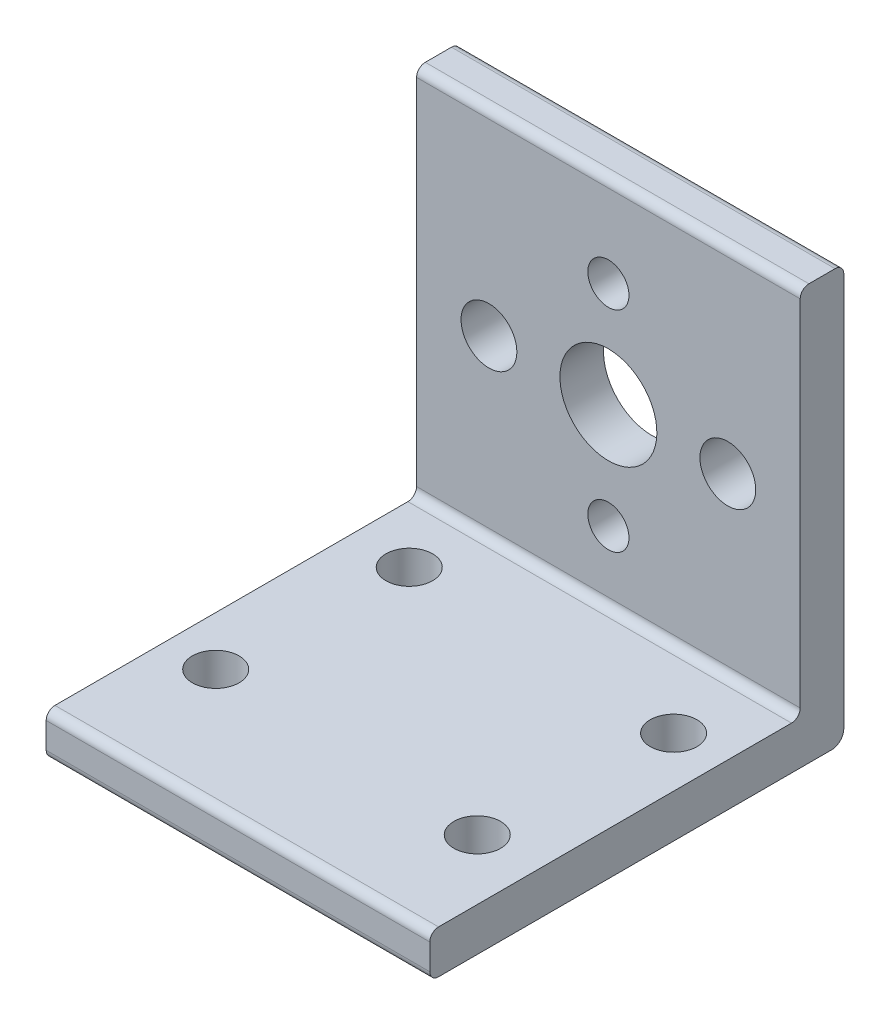
SolidWorks part; units mm, degrees
material "6061-T6 (SS)"
ref_plane "Front Plane" through (0, 0, 0) normal (0, 0, 1) x (1, 0, 0)
ref_plane "Top Plane" through (0, 0, 0) normal (0, 1, 0) x (1, 0, 0)
ref_plane "Right Plane" through (0, 0, 0) normal (1, 0, 0) x (0, 0, -1)
sketch "Sketch1" plane through (0, 0, 0) normal (1, 0, 0) x (0, 0, -1)
  line L0 (0, 0) -> (0, -30.226)
  line L1 (0, -30.226) -> (-30.1498, -30.226)
  line L2 (-30.1498, -30.226) -> (-30.1498, -27.0764)
  line L3 (-30.1498, -27.0764) -> (-3.175, -27.0764)
  line L4 (-3.175, -27.0764) -> (-3.175, 0)
  line L5 (-3.175, 0) -> (0, 0)
  dimension "D1" = 30.1498
  dimension "D2" = 30.226
  dimension "D3" = 3.175
  dimension "D4" = 3.1496
extrude "Boss-Extrude1" add sketch "Sketch1" along normal blind 27.94
sketch "Sketch2" plane through (0, 0, 0) normal (0, 0, 1) x (1, 0, 0)
  line L0 (13.97, -6.6548) -> (13.97, -21.9456) construction
  line L2 (27.94, 0) -> (0, 0) construction
  line L3 (5.2705, -14.3002) -> (22.6695, -14.3002) construction
  line L6 (0, -14.3002) -> (27.94, -14.3002) construction
  line L9 (0, 0) -> (0, -27.0764) construction
  line L10 (27.94, 0) -> (27.94, -27.0764) construction
  circle A0 centre (13.97, -14.3002) radius 3.5306
  circle A1 centre (13.97, -6.6548) radius 1.4986
  circle A2 centre (5.2705, -14.3002) radius 2.032
  circle A3 centre (22.6695, -14.3002) radius 2.032
  circle A4 centre (13.97, -21.9456) radius 1.4986
  point P0 (13.97, -14.3002)
  dimension "D1" = 7.0612
  dimension "D2" = 2.9972
  dimension "D3" = 14.3002
  dimension "D7" = 4.064
  dimension "D4" = 17.399
  dimension "D5" = 15.2908
extrude "Motor_Mount_holes" cut sketch "Sketch2" along normal through all
sketch "Sketch3" plane through (0, -30.226, 0) normal (0, 1, 0) x (1, 0, 0)
  line L0 (13.97, -3.175) -> (13.97, -30.1498) construction
  line L1 (27.94, -3.175) -> (0, -3.175) construction
  line L2 (27.94, -30.1498) -> (0, -30.1498) construction
  line L3 (27.94, 0) -> (0, 0) construction
  line L4 (27.94, -30.1498) -> (27.94, 0) construction
  line L5 (0, -14.5669) -> (28.2702, -14.5669) construction
  line L6 (27.94, 0) -> (0, 0) construction
  circle A4 centre (4.191, -7.8994) radius 1.7018
  circle A5 centre (24.2824, -8.7376) radius 1.7018
  circle A6 centre (3.5814, -21.3868) radius 1.7018
  circle A7 centre (23.5458, -22.3012) radius 1.7018
  dimension "D1" = 3.4036
  dimension "D2" = 8.7376
  dimension "D3" = 3.6576
  dimension "D4" = 22.3012
  dimension "D5" = 4.3942
  dimension "D6" = 7.8994
  dimension "D7" = 23.749
  dimension "D8" = 21.3868
  dimension "D9" = 24.3586
extrude "Plate_Mount_Holes" cut sketch "Sketch3" along normal through all
fillet "Fillet1" radius 0.635 1 edges at (13.97, -27.0764, 3.175)
fillet "Fillet2" radius 0.889 1 edges at (13.97, -30.226, 0)
fillet "Fillet3" radius 0.635 4 edges at (13.97, -30.226, 30.1498) (13.97, -27.0764, 30.1498) (13.97, 0, 0) (13.97, 0, 3.175)
